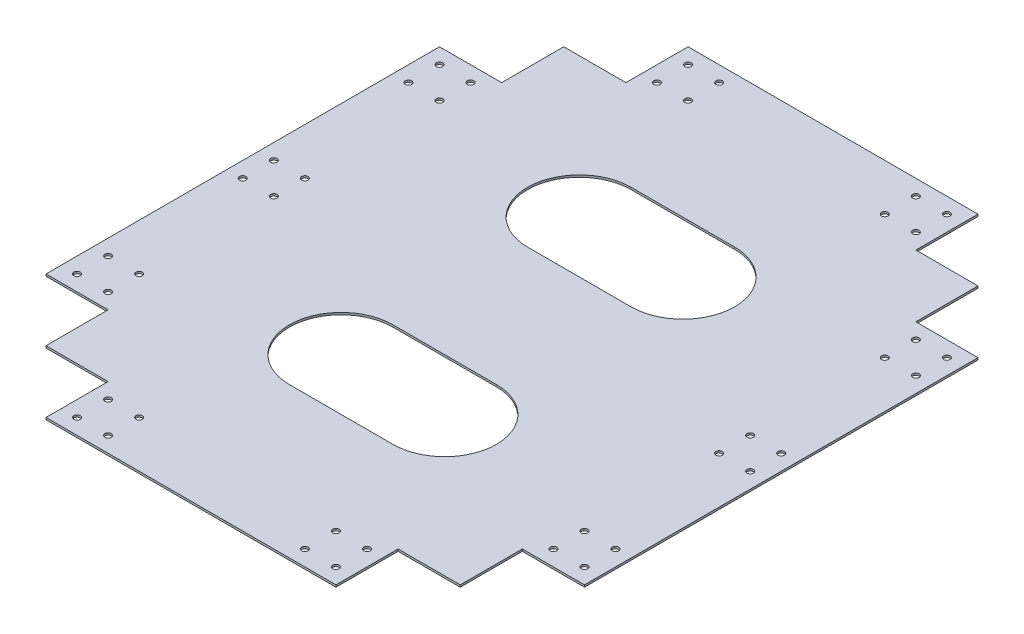
SolidWorks part; units mm, degrees
material "Thornel Mat VMA"
ref_plane "前视基准面" through (0, 0, 0) normal (0, 0, 1) x (1, 0, 0)
ref_plane "上视基准面" through (0, 0, 0) normal (0, 1, 0) x (1, 0, 0)
ref_plane "右视基准面" through (0, 0, 0) normal (1, 0, 0) x (0, 0, -1)
other "Configuration Table"
sketch "草图1" plane through (0, 0, 0) normal (0, 1, 0) x (1, 0, 0)
  line L0 (-187.6098, 175.8781) -> (-187.6098, 235.8781)
  line L1 (-127.6098, 295.8781) -> (152.3902, 295.8781)
  line L2 (212.3902, 235.8781) -> (212.3902, 175.8781)
  line L3 (212.3902, 175.8781) -> (272.3902, 175.8781)
  line L4 (272.3902, 175.8781) -> (272.3902, -204.1219)
  line L5 (272.3902, -204.1219) -> (212.3902, -204.1219)
  line L6 (212.3902, -204.1219) -> (212.3902, -264.1219)
  line L7 (152.3902, -324.1219) -> (-127.6098, -324.1219)
  line L8 (-187.6098, -264.1219) -> (-187.6098, -204.1219)
  line L9 (-187.6098, -204.1219) -> (-247.6098, -204.1219)
  line L10 (-247.6098, -204.1219) -> (-247.6098, 175.8781)
  line L11 (-247.6098, 175.8781) -> (-187.6098, 175.8781)
  line L12 (272.3902, 15.8781) -> (-247.6098, 15.8781)
  line L13 (-247.6098, -44.1219) -> (272.3902, -44.1219)
  line L14 (12.3902, -98.8347) -> (12.3902, -244.8347) construction
  line L19 (12.3902, 295.8781) -> (12.3902, -324.1219) construction
  line L20 (272.3902, -14.1219) -> (-247.6098, -14.1219) construction
  line L21 (-247.6098, -94.1219) -> (272.3902, -94.1219) construction
  line L22 (-37.6098, 100.8781) -> (62.3902, 100.8781) construction
  line L23 (-37.6098, 150.8781) -> (62.3902, 150.8781)
  line L24 (-37.6098, 50.8781) -> (62.3902, 50.8781)
  line L25 (-37.6098, -129.1219) -> (62.3902, -129.1219) construction
  line L26 (-37.6098, -179.1219) -> (62.3902, -179.1219)
  line L27 (-37.6098, -79.1219) -> (62.3902, -79.1219)
  line L28 (-187.6098, -264.1219) -> (-127.6098, -264.1219)
  line L29 (-127.6098, -264.1219) -> (-127.6098, -324.1219)
  line L30 (152.3902, -264.1219) -> (152.3902, -324.1219)
  line L31 (212.3902, -264.1219) -> (152.3902, -264.1219)
  line L32 (212.3902, 235.8781) -> (152.3902, 235.8781)
  line L33 (152.3902, 235.8781) -> (152.3902, 295.8781)
  line L34 (-127.6098, 235.8781) -> (-127.6098, 295.8781)
  line L35 (-187.6098, 235.8781) -> (-127.6098, 235.8781)
  circle A4 centre (-112.6098, -279.1219) radius 3.1
  circle A5 centre (-82.6098, -279.1219) radius 3.1
  circle A6 centre (-112.6098, -309.1219) radius 3.1
  circle A7 centre (-82.6098, -309.1219) radius 3.1
  circle A20 centre (-232.6098, -159.1219) radius 3.1
  circle A21 centre (-202.6098, -159.1219) radius 3.1
  circle A22 centre (-232.6098, -189.1219) radius 3.1
  circle A23 centre (-202.6098, -189.1219) radius 3.1
  circle A24 centre (257.3902, -189.1219) radius 3.1
  circle A25 centre (227.3902, -189.1219) radius 3.1
  circle A26 centre (227.3902, -159.1219) radius 3.1
  circle A27 centre (257.3902, -159.1219) radius 3.1
  circle A28 centre (227.3902, 160.8781) radius 3.1
  circle A29 centre (257.3902, 160.8781) radius 3.1
  circle A30 centre (257.3902, 130.8781) radius 3.1
  circle A31 centre (227.3902, 130.8781) radius 3.1
  circle A32 centre (-232.6098, 160.8781) radius 3.1
  circle A33 centre (-202.6098, 160.8781) radius 3.1
  circle A34 centre (-202.6098, 130.8781) radius 3.1
  circle A35 centre (-232.6098, 130.8781) radius 3.1
  circle A36 centre (-232.6098, 0.8781) radius 3.1
  circle A37 centre (-202.6098, 0.8781) radius 3.1
  circle A38 centre (-202.6098, -29.1219) radius 3.1
  circle A39 centre (-232.6098, -29.1219) radius 3.1
  circle A40 centre (257.3902, -29.1219) radius 3.1
  circle A41 centre (227.3902, -29.1219) radius 3.1
  circle A42 centre (227.3902, 0.8781) radius 3.1
  circle A43 centre (257.3902, 0.8781) radius 3.1
  arc A44 (-37.6098, 150.8781) -> (-37.6098, 50.8781) centre (-37.6098, 100.8781) ccw
  arc A45 (62.3902, 50.8781) -> (62.3902, 150.8781) centre (62.3902, 100.8781) ccw
  arc A46 (-37.6098, -179.1219) -> (-37.6098, -79.1219) centre (-37.6098, -129.1219) cw
  arc A47 (62.3902, -79.1219) -> (62.3902, -179.1219) centre (62.3902, -129.1219) cw
  circle A48 centre (137.3902, -309.1219) radius 3.1
  circle A49 centre (107.3902, -309.1219) radius 3.1
  circle A50 centre (107.3902, -279.1219) radius 3.1
  circle A51 centre (137.3902, -279.1219) radius 3.1
  circle A52 centre (107.3902, 280.8781) radius 3.1
  circle A53 centre (137.3902, 280.8781) radius 3.1
  circle A54 centre (137.3902, 250.8781) radius 3.1
  circle A55 centre (107.3902, 250.8781) radius 3.1
  circle A56 centre (-112.6098, 280.8781) radius 3.1
  circle A57 centre (-82.6098, 280.8781) radius 3.1
  circle A58 centre (-82.6098, 250.8781) radius 3.1
  circle A59 centre (-112.6098, 250.8781) radius 3.1
  point P16 (12.3902, 100.8781)
  point P116 (12.3902, -129.1219)
  dimension "D11" = 15
  dimension "D12" = 15
  dimension "D13" = 6.2
  dimension "D2" = 380
  dimension "D3" = 60
  dimension "D4" = 60
  dimension "D5" = 35
  dimension "D6" = 100
  dimension "D7" = 100
  dimension "D8" = 60
  dimension "D9" = 30
  dimension "D10" = 30
  dimension "D14" = 60
  dimension "D15" = 60
  dimension "D19" = 30
  dimension "D20" = 15
  dimension "D21" = 30
  dimension "D22" = 15
  dimension "D23" = 30
  dimension "D24" = 110
extrude "凸台-拉伸1" add sketch "草图1" along normal blind 2
